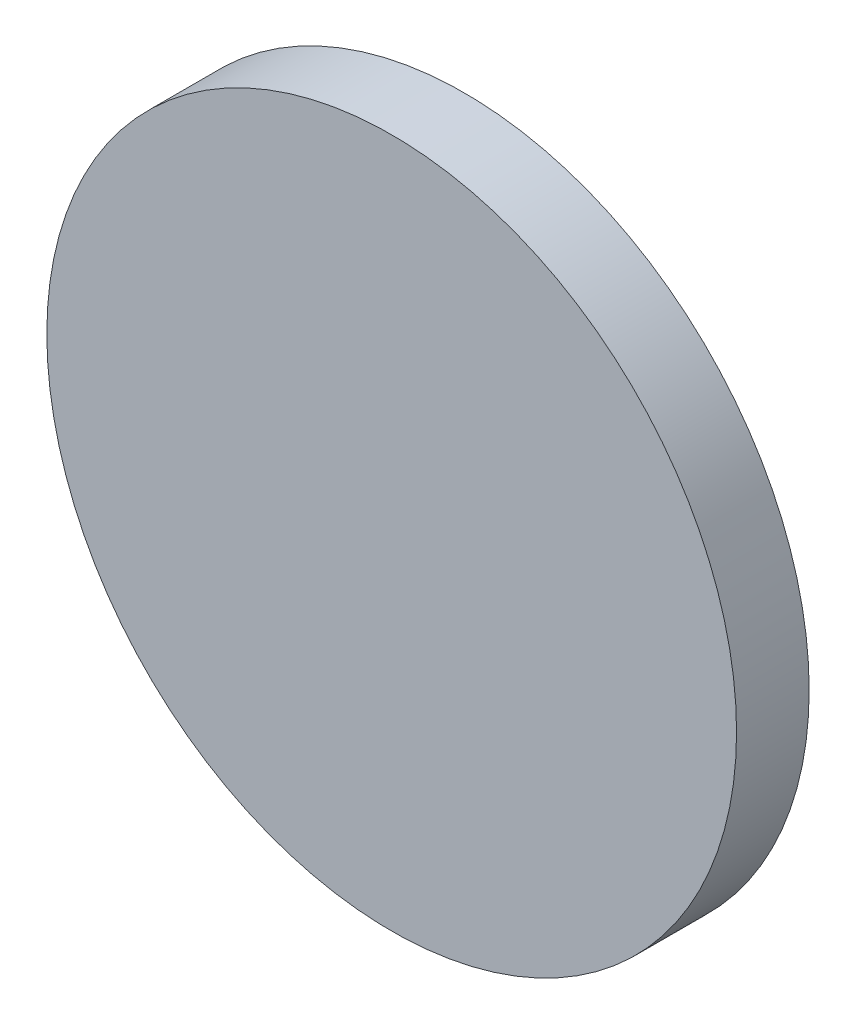
SolidWorks part; units mm, degrees
ref_plane "Front Plane" through (0, 0, 0) normal (0, 0, 1) x (1, 0, 0)
ref_plane "Top Plane" through (0, 0, 0) normal (0, 1, 0) x (1, 0, 0)
ref_plane "Right Plane" through (0, 0, 0) normal (1, 0, 0) x (0, 0, -1)
sketch "Sketch1" plane through (0, 0, 0) normal (0, 0, 1) x (1, 0, 0)
  circle A0 centre (0, 0) radius 30.1625
  dimension "D1" = 60.325
extrude "Boss-Extrude1" add sketch "Sketch1" along normal mid plane 6.35
